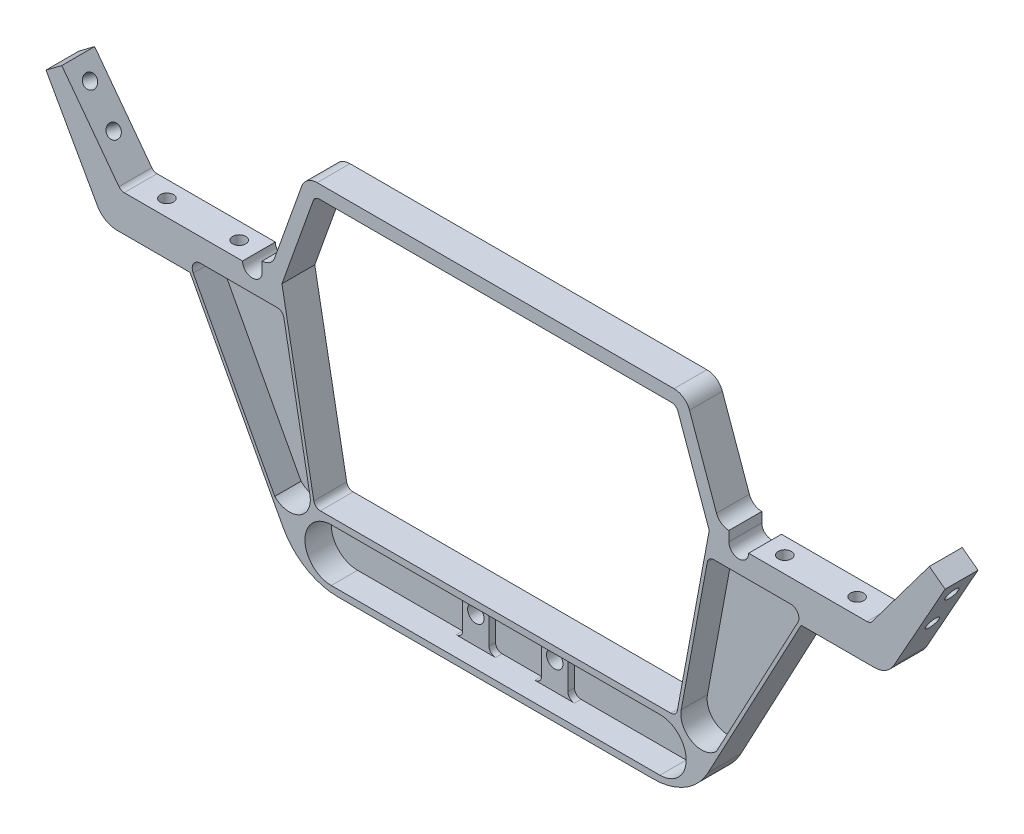
SolidWorks part; units mm, degrees
ref_plane "Alzado" through (0, 0, 0) normal (0, 0, 1) x (1, 0, 0)
ref_plane "Planta" through (0, 0, 0) normal (0, 1, 0) x (1, 0, 0)
ref_plane "Vista lateral" through (0, 0, 0) normal (1, 0, 0) x (0, 0, -1)
sketch "Croquis1" plane through (0, 0, 0) normal (0, 0, 1) x (1, 0, 0)
  line L1 (-69, -26.5) -> (69, -26.5)
  line L2 (-69, -26.5) -> (-69, 26.5)
  line L3 (-69, 26.5) -> (69, 26.5)
  line L4 (69, -26.5) -> (69, 26.5)
  line L5 (-69, -26.5) -> (69, 26.5) construction
  line L6 (-69, 26.5) -> (69, -26.5) construction
  point P0 (0, 0)
  dimension "D1" = 53
  dimension "D2" = 138
extrude "Saliente-Extruir1" add sketch "Croquis1" along normal blind 5
sketch "Croquis2" plane through (0, 0, 5) normal (0, 0, 1) x (1, 0, 0)
  line L0 (0, -26.5) -> (0, 26.5) construction
  line L1 (-69, -26.5) -> (69, -26.5) construction
  line L2 (69, 26.5) -> (-69, 26.5) construction
  line L3 (-27.5, -16.5) -> (27.5, -16.5)
  line L4 (27.5, -16.5) -> (32.5, 10.5)
  line L5 (32.5, 10.5) -> (27.5, 24.5)
  line L6 (27.5, 24.5) -> (-27.5, 24.5)
  line L7 (33.6131, 13.3297) -> (28.9094, 26.5)
  line L8 (28.9094, 26.5) -> (-28.9094, 26.5)
  line L9 (32.5, 10.5) -> (69, 10.5) construction
  line L10 (69, -26.5) -> (69, 26.5) construction
  line L11 (35.5, 10.5) -> (35.5, 12)
  line L12 (35.5, 12) -> (36.1642, 12) construction
  line L13 (38.5, 10.5) -> (57, 10.5)
  line L14 (57, 10.5) -> (65.9932, 22.5051)
  line L15 (65.9932, 22.5051) -> (68.3943, 20.7064)
  line L16 (68.3943, 20.7064) -> (59.6008, 5)
  line L17 (59.6008, 5) -> (46.4815, 5)
  line L18 (46.4815, 5) -> (29.6598, -26.5)
  line L19 (29.6598, -26.5) -> (-29.6598, -26.5)
  line L20 (61.4966, 16.5025) -> (64.698, 14.1043) construction
  line L21 (46.4815, 5) -> (31.4815, 5) construction
  line L22 (27.5, -16.5) -> (35, -16.5) construction
  line L23 (-27.5, -16.5) -> (-35, -16.5) construction
  line L24 (-46.4815, 5) -> (-31.4815, 5) construction
  line L25 (-61.4966, 16.5025) -> (-64.698, 14.1043) construction
  line L26 (-35.5, 12) -> (-36.1642, 12) construction
  line L27 (-32.5, 10.5) -> (-69, 10.5) construction
  line L28 (-46.4815, 5) -> (-29.6598, -26.5)
  line L29 (-59.6008, 5) -> (-46.4815, 5)
  line L30 (-68.3943, 20.7064) -> (-59.6008, 5)
  line L31 (-65.9932, 22.5051) -> (-68.3943, 20.7064)
  line L32 (-57, 10.5) -> (-65.9932, 22.5051)
  line L33 (-38.5, 10.5) -> (-57, 10.5)
  line L34 (-35.5, 10.5) -> (-35.5, 12)
  line L35 (-33.6131, 13.3297) -> (-28.9094, 26.5)
  line L36 (-32.5, 10.5) -> (-27.5, 24.5)
  line L37 (-27.5, -16.5) -> (-32.5, 10.5)
  circle A0 centre (6, -21.25) radius 1.25
  circle A2 centre (37, 10.5) radius 1.5
  circle A3 centre (35.5, 14.0036) radius 2.0036
  circle A4 centre (-35.5, 14.0036) radius 2.0036
  circle A5 centre (-37, 10.5) radius 1.5
  circle A6 centre (-6, -21.25) radius 1.25
  point P13 (0, -16.5)
  point P62 (0, 24.5)
  line M16 (69, -26.5) -> (69, 26.5)
  line M17 (69, 26.5) -> (-69, 26.5)
  line M18 (-69, 26.5) -> (-69, -26.5)
  line M19 (-69, -26.5) -> (69, -26.5)
  dimension "D1" = 6
  dimension "D2" = 5.25
  dimension "D3" = 2.5
  dimension "D13" = 3
  dimension "D4" = 10
  dimension "D5" = 27.5
  dimension "D6" = 37
  dimension "D7" = 32.5
  dimension "D8" = 2
  dimension "D9" = 5
  dimension "D10" = 2
  dimension "D11" = 1.5
  dimension "D12" = 3
  dimension "D14" = 18.5
  dimension "D15" = 3
  dimension "D16" = 15
  dimension "D17" = 30
  dimension "D18" = 5.5
  dimension "D19" = 4
  dimension "D20" = 15
  dimension "D21" = 7.5
extrude "Principal" cut sketch "Croquis2" against normal blind 5 contours L37 L3 L4 L5 L6 L36 | L33 A5 L34 A4 L35 L28 L29 L30 L31 L32 M17 M18 M19 | A3 L11 A2 L13 L14 L15 L16 L17 L18 L7 M19 M16 M17 | A4 | A3 | A2 | A5 | A6 | A0
sketch "Croquis3" plane through (0, 0, 5) normal (0, 0, 1) x (1, 0, 0)
  line L0 (0, -26.5) -> (0, 26.5) construction
  line L1 (-29.6598, -26.5) -> (29.6598, -26.5) construction
  line L2 (28.9094, 26.5) -> (-28.9094, 26.5) construction
  line L3 (0, -26.5) -> (29.6598, -26.5)
  line L4 (29.6598, -26.5) -> (46.4815, 5)
  line L5 (46.4815, 5) -> (59.6008, 5)
  line L6 (59.6008, 5) -> (68.3943, 20.7064)
  line L7 (68.3943, 20.7064) -> (65.9932, 22.5051)
  line L8 (65.9932, 22.5051) -> (57, 10.5)
  line L9 (57, 10.5) -> (38.5, 10.5)
  line L10 (38.5, 10.5) -> (35.5, 12)
  line L11 (35.5, 12) -> (32.9733, 15.1212)
  line L12 (33.6131, 13.3297) -> (28.9094, 26.5) construction
  line L13 (32.9733, 15.1212) -> (28.9094, 26.5)
  line L14 (28.9094, 26.5) -> (0, 26.5)
  line L15 (0, 24.5) -> (27.5, 24.5)
  line L16 (27.5, 24.5) -> (-27.5, 24.5) construction
  line L17 (27.5, 24.5) -> (32.5, 10.5)
  line L18 (32.5, 10.5) -> (27.5, -16.5)
  line L19 (27.5, -16.5) -> (0, -16.5)
  line L20 (-27.5, -16.5) -> (27.5, -16.5) construction
  line L21 (46.4815, 5) -> (57.6003, 5) construction
  line L22 (68.3943, 20.7064) -> (60.578, 6.7455) construction
  line L25 (0, -26.5) -> (24, -26.5) construction
  line L26 (46.4815, 5) -> (32.3259, -21.5075) construction
  circle A2 centre (27.1476, 24) radius 2.5
  circle A4 centre (24, -17.0613) radius 9.4387
  circle A6 centre (57.6003, 8.4127) radius 3.4127
  line M24 (29.6598, -26.5) -> (46.4815, 5)
  line M26 (59.6008, 5) -> (68.3943, 20.7064)
  line M34 (28.9094, 26.5) -> (-28.9094, 26.5)
  dimension "D1" = 5
  dimension "D2" = 16
  dimension "D3" = 24
extrude "Cortar-Extruir2" cut sketch "Croquis3" against normal blind 5 contours A4 L3 M24 | A6 L5 M26 | A2 L13 M34
mirror "Simetría2" about plane through (0, 0, 0) normal (1, 0, 0) of "Cortar-Extruir2"
sketch "Croquis4" plane through (0, 0, 5) normal (0, 0, 1) x (1, 0, 0)
  line L0 (0, -16.5) -> (27.5, -16.5)
  line L1 (-27.5, -16.5) -> (27.5, -16.5) construction
  line L2 (27.5, -16.5) -> (32.5, 10.5)
  line L3 (32.5, 10.5) -> (27.5, 24.5)
  line L4 (27.5, 24.5) -> (0, 24.5)
  line L5 (27.5, 24.5) -> (-27.5, 24.5) construction
  line L6 (38.5, 10.5) -> (57, 10.5)
  line L7 (57, 10.5) -> (65.9932, 22.5051)
  circle A0 centre (26.7953, 23.5) radius 1
  circle A1 centre (26.6682, -15.5) radius 1
  circle A2 centre (56.4996, 11.5) radius 1
  line M6 (27.5, 24.5) -> (32.5, 10.5)
  line M8 (27.5, -16.5) -> (-27.5, -16.5)
  line M20 (57, 10.5) -> (38.5, 10.5)
  dimension "D1" = 2
  dimension "D2" = 2
  dimension "D3" = 2
extrude "Saliente-Extruir2" add sketch "Croquis4" against normal blind 5 contours A1 L2 M8 | A0 L4 M6 | A2 L7 M20
mirror "Simetría3" about plane through (0, 0, 0) normal (1, 0, 0) of "Saliente-Extruir2"
sketch "Croquis5" plane through (0, 0, 5) normal (0, 0, 1) x (1, 0, 0)
  line L0 (28.2386, -15.2576) -> (32.3604, 7)
  line L1 (32.3604, 7) -> (46.9827, 7)
  line L2 (46.9827, 7) -> (33.5968, -18.0661)
  line L3 (27.6515, -15.6821) -> (32.0643, 8.1471) construction
  line L4 (27.6515, -15.6821) -> (32.5, 10.5) construction
  line L5 (32.6054, -20.9841) -> (45.8056, 3.7344) construction
  line L6 (46.4815, 5) -> (32.3259, -21.5075) construction
  line L7 (38.5, 10.5) -> (54.7175, 10.5) construction
  line L8 (38.5, 10.5) -> (56.4996, 10.5) construction
  line L9 (26.6682, -16.5) -> (26.6682, -19) construction
  line L10 (26.6682, -19) -> (31.3516, -19) construction
  arc A1 (28.2386, -15.2576) -> (33.5968, -18.0661) centre (31.3516, -15.8341) ccw
  circle A2 centre (33.1922, 6) radius 1
  circle A3 centre (44.8981, 5.75) radius 1.25
  dimension "D6" = 2
  dimension "D7" = 2.5
  dimension "D1" = 1
  dimension "D2" = 1
  dimension "D3" = 3.5
  dimension "D4" = 2.5
extrude "Cortar-Extruir3" cut sketch "Croquis5" against normal blind 4 contours A3 L1 A2 L0 A1 L2 | A2 | A3
mirror "Simetría4" about plane through (0, 0, 0) normal (1, 0, 0) of "Cortar-Extruir3"
sketch "Croquis6" plane through (0, 0, 5) normal (0, 0, 1) x (1, 0, 0)
  line L0 (-25, -17.5) -> (25, -17.5)
  line L1 (25, -25.5) -> (-25, -25.5)
  line L2 (-26.6682, -16.5) -> (26.6682, -16.5) construction
  line L3 (-24, -26.5) -> (24, -26.5) construction
  line L4 (0, -17.5) -> (0, -16.5) construction
  circle A0 centre (-25, -21.5) radius 4
  circle A1 centre (25, -21.5) radius 4
  dimension "D1" = 1
  dimension "D2" = 1
  dimension "D3" = 50
extrude "Cortar-Extruir4" cut sketch "Croquis6" against normal blind 4 contours A0 | A1 L0 A0 L1 | A1
sketch "Croquis8" plane through (0, 0, 1) normal (0, 0, 1) x (1, 0, 0)
  line L0 (4, -17.5) -> (4, -25.5)
  line L1 (-25, -17.5) -> (25, -17.5) construction
  line L2 (25, -25.5) -> (-25, -25.5) construction
  line L3 (8, -17.5) -> (8, -25.5)
  line L4 (4, -17.5) -> (8, -17.5)
  line L5 (4, -25.5) -> (8, -25.5)
  line L6 (8, -17.5) -> (9, -17.5)
  line L7 (-25, -17.5) -> (25, -17.5) construction
  line L8 (4, -17.5) -> (3, -17.5)
  line L9 (4, -25.5) -> (3, -25.5)
  line L10 (25, -25.5) -> (-25, -25.5) construction
  line L11 (8, -25.5) -> (9, -25.5)
  circle A0 centre (6, -21.25) radius 1.25
  circle A1 centre (3, -18.5) radius 1
  circle A2 centre (9, -18.5) radius 1
  circle A3 centre (3, -24.5) radius 1
  circle A4 centre (9, -24.5) radius 1
  line M13 (-25, -25.5) -> (25, -25.5)
  line M15 (25, -17.5) -> (-25, -17.5)
  circle M16 centre (6, -21.25) radius 1.25
  dimension "D1" = 2
  dimension "D2" = 2
  dimension "D3" = 1
  dimension "D4" = 1
  dimension "D5" = 1
  dimension "D6" = 1
extrude "Saliente-Extruir3" add sketch "Croquis8" along normal blind 1 contours A1 L0 M15 | L3 L0 M15 M13 M16 | A2 L3 M15 | A4 L3 M13 | A3 L9 L0
mirror "Simetría5" about plane through (0, 0, 0) normal (1, 0, 0) of "Saliente-Extruir3"
sketch "Croquis9" plane through (31.4725, -23.5767, 0) normal (-0.8003, 0.5995, 0) x (0, 0, 1)
  line L0 (0, 57.5779) -> (5, 57.5779) construction
  line L1 (2.5, 57.5779) -> (2.5, 55.5779) construction
  circle A0 centre (2.5, 54.5779) radius 1
  circle A1 centre (2.5, 48.5779) radius 1
  dimension "D1" = 2
  dimension "D2" = 2
  dimension "D4" = 6
  dimension "D3" = 2
extrude "Cortar-Extruir5" cut sketch "Croquis9" against normal blind 10
mirror "Simetría6" about plane through (0, 0, 0) normal (1, 0, 0) of "Cortar-Extruir5"
sketch "Croquis10" plane through (0, 10.5, 0) normal (0, 1, 0) x (1, 0, 0)
  line L0 (56.4996, 0) -> (56.4996, -5) construction
  line L1 (35.5, -2.5) -> (40.5, -2.5) construction
  line L2 (35.5, 0) -> (35.5, -5) construction
  circle A0 centre (52.5, -2.5) radius 1
  circle A1 centre (41.5, -2.5) radius 1
  dimension "D1" = 2
  dimension "D2" = 2
  dimension "D4" = 11
  dimension "D3" = 5
extrude "Cortar-Extruir6" cut sketch "Croquis10" against normal blind 10
mirror "Simetría7" about plane through (0, 0, 0) normal (1, 0, 0) of "Cortar-Extruir6"
